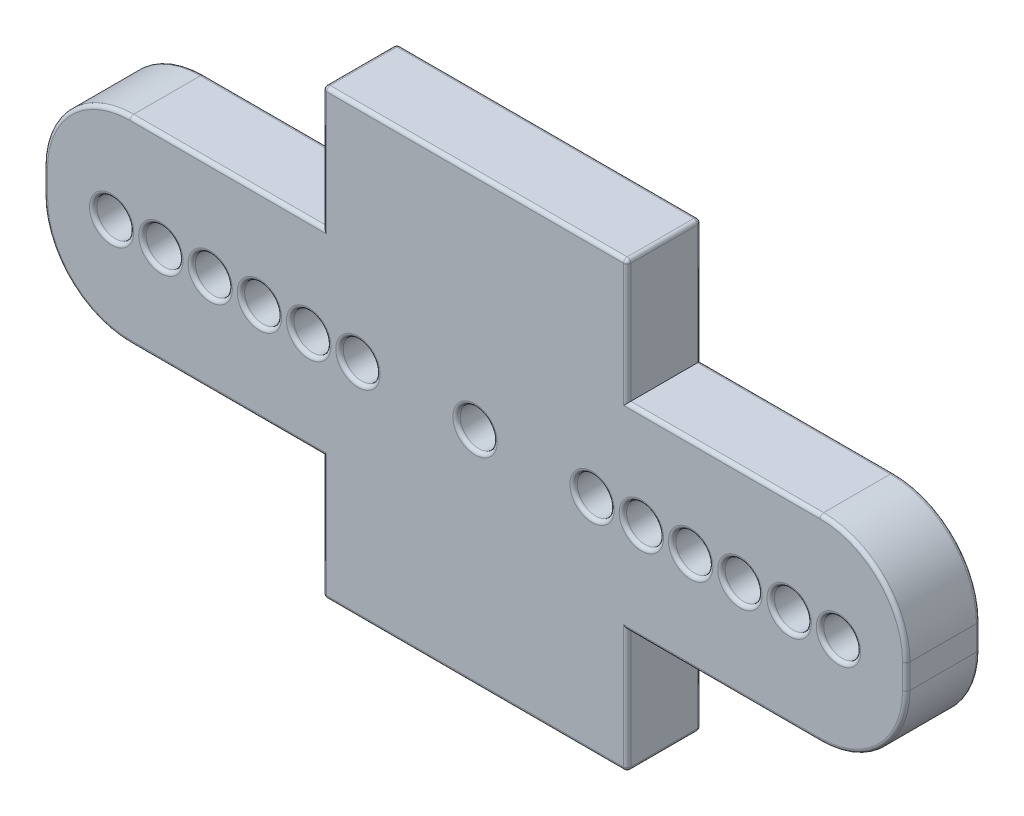
SolidWorks part; units mm, degrees
ref_plane "Front Plane" through (0, 0, 0) normal (0, 0, 1) x (1, 0, 0)
ref_plane "Top Plane" through (0, 0, 0) normal (0, 1, 0) x (1, 0, 0)
ref_plane "Right Plane" through (0, 0, 0) normal (1, 0, 0) x (0, 0, -1)
sketch "Sketch1" plane through (0, 0, 0) normal (0, 0, 1) x (1, 0, 0)
  line L0 (-14, 4) -> (-6.175, 4)
  line L1 (17.5, -4) -> (-17.5, -4) construction
  line L2 (17.5, -4) -> (17.5, 4) construction
  line L3 (17.5, 4) -> (-17.5, 4) construction
  line L4 (-17.5, -4) -> (-17.5, 4) construction
  line L5 (17.5, -4) -> (-17.5, 4) construction
  line L6 (17.5, 4) -> (-17.5, -4) construction
  line L7 (6.175, -9) -> (-6.175, -9) construction
  line L8 (6.175, -9) -> (6.175, 9) construction
  line L9 (6.175, 9) -> (-6.175, 9) construction
  line L10 (-6.175, -9) -> (-6.175, 9) construction
  line L11 (6.175, -9) -> (-6.175, 9) construction
  line L12 (6.175, 9) -> (-6.175, -9) construction
  line L13 (-6.175, 4) -> (-6.175, 9)
  line L14 (-6.175, 9) -> (6.175, 9)
  line L15 (6.175, 9) -> (6.175, 4)
  line L16 (6.175, 4) -> (14, 4)
  line L17 (17.5, 0.5) -> (17.5, -0.5)
  line L18 (14, -4) -> (6.175, -4)
  line L19 (6.175, -4) -> (6.175, -9)
  line L20 (6.175, -9) -> (-6.175, -9)
  line L21 (-6.175, -9) -> (-6.175, -4)
  line L22 (-6.175, -4) -> (-14, -4)
  line L23 (-17.5, -0.5) -> (-17.5, 0.5)
  circle A0 centre (0, 0) radius 0.75
  arc A1 (14, 4) -> (17.5, 0.5) centre (14, 0.5) cw
  arc A2 (17.5, -0.5) -> (14, -4) centre (14, -0.5) cw
  arc A3 (-14, -4) -> (-17.5, -0.5) centre (-14, -0.5) cw
  arc A4 (-14, 4) -> (-17.5, 0.5) centre (-14, 0.5) ccw
  point P0 (0, 0)
  point P6 (0, 0)
  dimension "D5" = 1.5
  dimension "D6" = 3.5
  dimension "D1" = 8
  dimension "D2" = 12.35
  dimension "D3" = 18
  dimension "D4" = 35
extrude "Boss-Extrude1" add sketch "Sketch1" along normal mid plane 3
sketch "Sketch2" plane through (0, 0, 1.5) normal (0, 0, 1) x (1, 0, 0)
  line L0 (-17.5, 0) -> (18.7814, 0) construction
  line L1 (-17.5, 0.5) -> (-17.5, -0.5) construction
  circle A0 centre (-14.75, 0) radius 0.75
  circle A1 centre (-12.75, 0) radius 0.75
  circle A2 centre (-10.75, 0) radius 0.75
  circle A3 centre (-8.75, 0) radius 0.75
  circle A4 centre (-6.75, 0) radius 0.75
  circle A5 centre (-4.75, 0) radius 0.75
  dimension "D2" = 1.5
  dimension "D1" = 2.75
  dimension "D4" = 2
  dimension "D3" = 6
extrude "Cut-Extrude1" cut sketch "Sketch2" against normal through all
mirror "Mirror1" about plane through (0, 0, 0) normal (1, 0, 0) of "Cut-Extrude1"
fillet "Fillet2" radius 0.15 62 edges at (4, 0, 1.5) (4, 0, -1.5) (6, 0, 1.5) (6, 0, -1.5) (8, 0, 1.5) (8, 0, -1.5) (10, 0, 1.5) (10, 0, -1.5) (12, 0, 1.5) (12, 0, -1.5) (14, 0, 1.5) (14, 0, -1.5) (-4, 0, 1.5) (-4, 0, -1.5) (-6, 0, 1.5) (-6, 0, -1.5) (-8, 0, 1.5) (-8, 0, -1.5) (-10, 0, 1.5) (-10, 0, -1.5) (-12, 0, 1.5) (-12, 0, -1.5) (-14, 0, 1.5) (-14, 0, -1.5) (0.75, 0, -1.5) (0.75, 0, 1.5) (-17.5, 0, -1.5) (-10.0875, -4, -1.5) (-6.175, -6.5, -1.5) (0, -9, -1.5) (6.175, -6.5, -1.5) (10.0875, -4, -1.5) (17.5, 0, -1.5) (10.0875, 4, -1.5) (6.175, 6.5, -1.5) (0, 9, -1.5) (-6.175, 6.5, -1.5) (-10.0875, 4, -1.5) (-17.5, 0, 1.5) (-10.0875, -4, 1.5) (-6.175, -6.5, 1.5) (0, -9, 1.5) (6.175, -6.5, 1.5) (10.0875, -4, 1.5) (17.5, 0, 1.5) (10.0875, 4, 1.5) (6.175, 6.5, 1.5) (0, 9, 1.5) (-6.175, 6.5, 1.5) (-10.0875, 4, 1.5) (-6.175, 9, 0) (6.175, 9, 0) (6.175, -9, 0) (-6.175, -9, 0) (16.4749, -2.9749, -1.5) (16.4749, 2.9749, -1.5) (-16.4749, -2.9749, -1.5) (-16.4749, 2.9749, -1.5) (16.4749, -2.9749, 1.5) (16.4749, 2.9749, 1.5) (-16.4749, -2.9749, 1.5) (-16.4749, 2.9749, 1.5)
